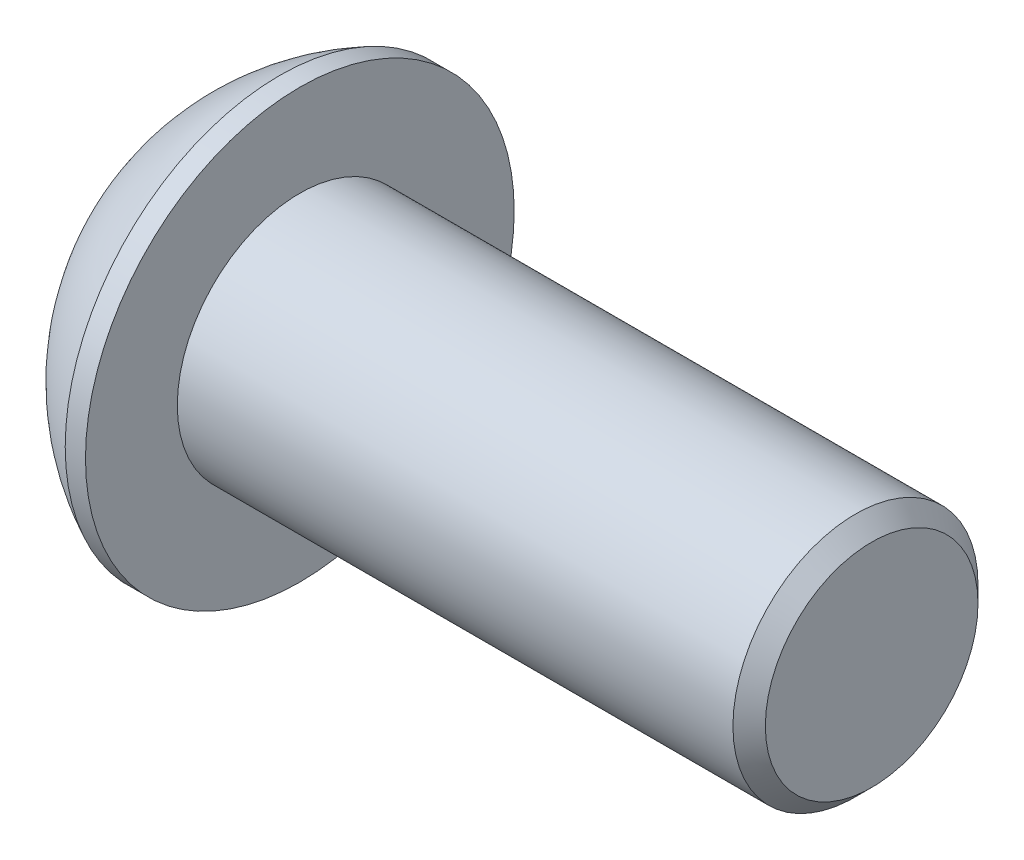
SolidWorks part; units mm, degrees
ref_plane "Plane1" through (0, 0, 0) normal (0, 0, 1) x (1, 0, 0)
ref_plane "Plane2" through (0, 0, 0) normal (0, 1, 0) x (1, 0, 0)
ref_plane "Plane3" through (0, 0, 0) normal (1, 0, 0) x (0, 0, -1)
sketch "BodySke" plane through (0, 0, 0) normal (0, 0, 1) x (1, 0, 0)
  line L0 (27.2796, 0) -> (27.2796, 4.1326)
  line L1 (26.6497, 4.7625) -> (5.0546, 4.7625)
  line L2 (5.0546, 4.7625) -> (5.0546, 8.3312)
  line L3 (5.0546, 8.3312) -> (4.2672, 8.3312)
  line L4 (0, 0) -> (101.6, 0) construction
  line L5 (5.0546, -8.3312) -> (4.2672, -8.3312) construction
  line L6 (55.6768, -4.7625) -> (5.0546, -4.7625) construction
  line L7 (27.2796, 0) -> (0, 0)
  line L8 (0, 4.1656) -> (0, -4.1656) construction
  line L9 (0, 0) -> (0, 4.1656)
  line L10 (27.2796, 4.1326) -> (26.6497, 4.7625)
  line L11 (27.2796, -4.1326) -> (26.6497, -4.7625) construction
  line L12 (6.1138, 9.525) -> (6.1138, -4.7625) construction
  line L13 (5.0546, 9.525) -> (5.0546, -4.7625) construction
  arc A1 (0, 4.1656) -> (4.2672, 8.3312) centre (8.2332, 0) cw
  dimension "Diameter" = 9.525
  dimension "Length" = 22.225
  dimension "Head_dia" = 16.6624
  dimension "D1" = 8.3312
  dimension "Head_ht" = 5.0546
  dimension "Head_side_ht" = 0.7874
  dimension "Minor_dia" = 8.2652
  dimension "Body_ch_ang" = 45
  dimension "Advance" = 1.0592
  dimension "Thread_nom" = 22.225
revolve "BaseBody" add sketch "BodySke" angle 360 about L4
cosmetic thread "ThreadCosmetic" [suppressed] parameters "Thread_length"=21.1658, "Thread_minor"=8.2652
sketch "Sketch2" plane through (0, 0, 0) normal (0, 0, 1) x (1, 0, 0)
  line L0 (0, 2.7813) -> (3.0988, 2.7813)
  line L1 (3.0988, 2.7813) -> (4.7046, 0)
  line L3 (4.7046, 0) -> (0, 0)
  line L4 (0, 0) -> (0, 2.7813)
  line L5 (0, -2.7813) -> (3.0988, -2.7813) construction
  line L6 (0, 0) -> (47.625, 0) construction
  dimension "D2" = 60
  dimension "PreBroach_depth" = 3.0988
  dimension "PreBroach_dia" = 5.5626
revolve "PreBroach" cut sketch "Sketch2" angle 360 about L6
sketch "Sketch3" plane through (0, 0, 0) normal (1, 0, 0) x (0, 0, -1)
  line L0 (-2.7813, -1.6058) -> (-2.7813, 1.6058)
  line L1 (-2.7813, 1.6058) -> (0, 3.2116)
  line L2 (0, 3.2116) -> (2.7813, 1.6058)
  line L3 (2.7813, 1.6058) -> (2.7813, -1.6058)
  line L4 (2.7813, -1.6058) -> (0, -3.2116)
  line L5 (0, -3.2116) -> (-2.7813, -1.6058)
  dimension "Hex_size" = 5.5626
  dimension "D3" = 5.5626
  dimension "D1" = 2.7813
  dimension "D2" = 2.7813
extrude "Hex" cut sketch "Sketch3" along normal blind 3.0988
sketch "Sketch4" plane through (0, 9.525, 0) normal (1, 0, 0) x (0, 0, -1)
  line L0 (0, -9.525) -> (3.2512, -9.525)
  line L1 (0, -9.525) -> (6.1484, -5.9752) construction
  line L2 (0, -9.525) -> (1.6256, -6.7094)
  line L3 (2.7204, -8.8343) -> (3.1182, -8.6046)
  line L4 (1.9584, -7.5144) -> (2.3562, -7.2848)
  arc A0 (2.7204, -8.8343) -> (1.9584, -7.5144) centre (0, -9.525) ccw
  arc A1 (3.2512, -9.525) -> (3.1182, -8.6046) centre (0, -9.525) ccw
  arc A2 (1.6256, -6.7094) -> (2.3562, -7.2848) centre (0, -9.525) cw
  dimension "Spline_n_dim" = 5.6134
  dimension "Spline_m_dim" = 6.5024
  dimension "D1" = 30
  dimension "D2" = 60
  dimension "Spline_p_dim" = 1.524
  dimension "D3" = 0.762
extrude "Spline" [suppressed] cut sketch "Sketch4" along normal blind 3.0988
pattern_circular "CirPattern1" [suppressed] count 6 every 60 about axis through (0, 0, 0) along (1, 0, 0)
sketch "ThdSchSke" plane through (0, 0, 0) normal (0, 0, 1) x (1, 0, 0)
  line L0 (6.1138, -4.1326) -> (5.6727, -4.7625)
  line L1 (6.1138, -4.1326) -> (6.5549, -4.7625)
  line L2 (6.5549, -4.7625) -> (6.5549, -5.9531)
  line L3 (-3.175, 0) -> (5.1513, 0) construction
  line L5 (6.5549, -5.9531) -> (5.6727, -5.9531)
  line L6 (5.6727, -5.9531) -> (5.6727, -4.7625)
  dimension "Diameter" = 9.525
  dimension "Thread_minor" = 8.2652
  dimension "SideAngle" = 55
  dimension "VeeAngle" = 70
  dimension "Overcut" = 11.9063
  dimension "Start" = 6.1138
revolve "ThreadSchematic" [suppressed] cut sketch "ThdSchSke" angle 360 about L3
pattern_linear "ThdSchPat" [suppressed]
equation "\"D1@BodySke\" = \"Head_dia@BodySke\" * .5"
equation "\"Thread_minor@ThreadCosmetic\" = \"Minor_dia@BodySke\""
equation "\"D1@Sketch3\" = \"Hex_size@Sketch3\" / 2"
equation "\"D2@Sketch3\" = \"D1@Sketch3\""
equation "\"D3@Sketch3\" = \"Hex_size@Sketch3\""
equation "\"D3@Sketch4\" = \"Spline_p_dim@Sketch4\" / 2"
equation "\"D1@Sketch4\" = \"D2@Sketch4\" / 2"
equation "\"Thread_length@ThreadCosmetic\" = ((sgn( (\"Length@BodySke\" - \"Advance@BodySke\" ) - \"Thread_nom@BodySke\" )-1)*( (\"Length@BodySke\" - \"Advance@BodySke\" ) - \"Thread_nom@BodySke\" ))/-2+ \"Thread_nom@BodySke\""
equation "\"Thread_minor@ThdSchSke\" = \"Minor_dia@BodySke\""
equation "\"Diameter@ThdSchSke\" = \"Diameter@BodySke\""
equation "\"Overcut@ThdSchSke\" = \"Diameter@BodySke\" * 1.25"
equation "\"Start@ThdSchSke\" = \"Head_ht@BodySke\" + \"Length@BodySke\" - \"Thread_length@ThreadCosmetic\"  '---Non-countersunk---"
equation "\"Num_threads@ThdSchPat\" = int( \"Thread_length@ThreadCosmetic\" / \"Advance@BodySke\" + 0.999 )  + 1"
equation "\"Advance@ThdSchPat\" = \"Thread_length@ThreadCosmetic\" /  (\"Num_threads@ThdSchPat\" - 1) 'relax it"
equation "\"Num_threads@ThdSchPat\" = \"Num_threads@ThdSchPat\" - sgn( \"Num_threads@ThdSchPat\" - 1) '---chamfered tips only---"
